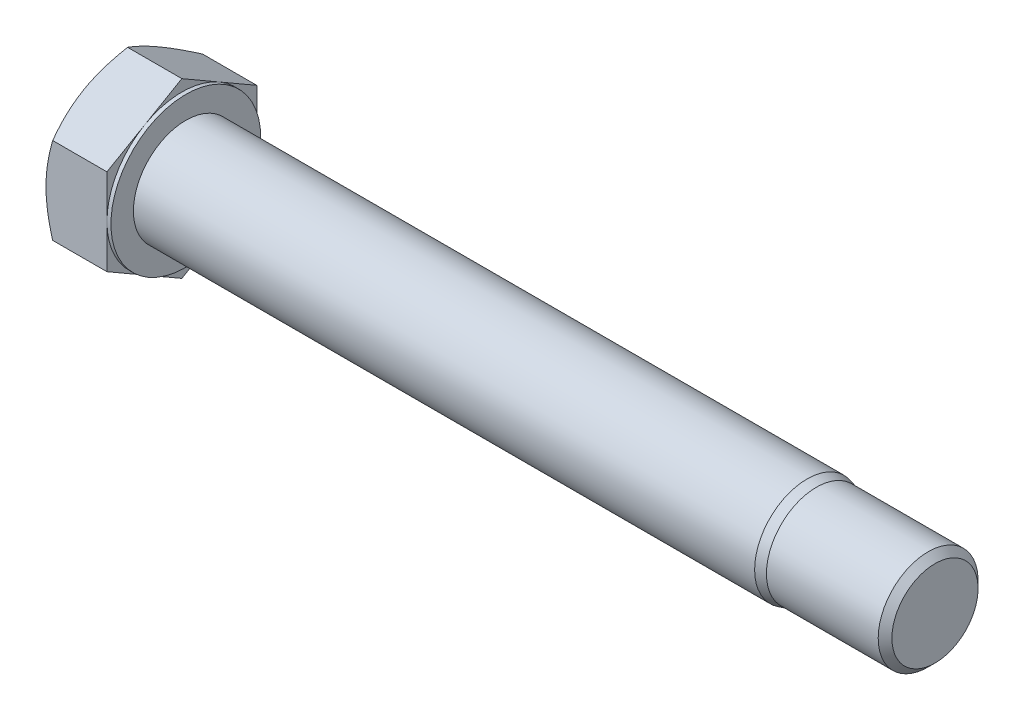
SolidWorks part; units mm, degrees
extrude "BaseHead" add sketch "HeadSke" along normal blind 13
sketch "HeadSke" plane through (0, 0, 0) normal (1, 0, 0) x (0, 0, -1)
  line L0 (15, 8.6603) -> (15, -8.6603)
  line L1 (-15, 8.6603) -> (-15, -8.6603)
  line L2 (15, -8.6603) -> (0, -17.3205)
  line L3 (0, -17.3205) -> (-15, -8.6603)
  line L4 (15, 8.6603) -> (0, 17.3205)
  line L5 (0, 17.3205) -> (-15, 8.6603)
  line L6 (0, 17.3205) -> (0, -17.3205) construction
  dimension "Width_flats" = 30
  dimension "D2" = 120
ref_plane "Plane1" through (0, 0, 0) normal (0, 0, 1) x (1, 0, 0)
ref_plane "Plane2" through (0, 0, 0) normal (0, 1, 0) x (1, 0, 0)
ref_plane "Plane3" through (0, 0, 0) normal (1, 0, 0) x (0, 0, -1)
sketch "BodySke" plane through (0, 0, 0) normal (0, 0, 1) x (1, 0, 0)
  line L0 (0, 10.5) -> (0, 0)
  line L2 (0, 0) -> (163, 0)
  line L4 (163, 0) -> (163, 8.626)
  line L5 (13, 17.3205) -> (13, 8.6603) construction
  line L6 (163, 8.626) -> (161.626, 10)
  line L7 (0, 0) -> (194.2747, 0) construction
  line L8 (163, -8.626) -> (161.626, -10) construction
  line L9 (0, -10) -> (161.626, -10) construction
  line L10 (15.5, 15.24) -> (15.5, -1.27) construction
  line L11 (139.25, 10) -> (137.384, 10.5)
  line L12 (13, 8.6603) -> (13, -8.6603) construction
  line L13 (137.384, 10.5) -> (0, 10.5)
  line L15 (139.25, 10) -> (161.626, 10)
  dimension "D1" = 75
  dimension "Diameter" = 20
  dimension "Thread_nom" = 23.75
revolve "BaseBody" add sketch "BodySke" angle 360 about L7
cosmetic thread "ThreadCosmetic" [suppressed] parameters "Thread_length"=21.25, "Thread_minor"=17.252
sketch "Sketch3" plane through (0, 0, 0) normal (0, 1, 0) x (1, 0, 0)
  line L0 (3.75, 21.4952) -> (-3.75, 8.5048)
  line L1 (3.75, 21.4952) -> (-6.1958, 27.2374)
  line L2 (-3.75, 8.5048) -> (-13.6958, 14.247)
  line L3 (-6.1958, 27.2374) -> (-13.6958, 14.247)
  line L4 (0, 15) -> (0, 0) construction
  line L6 (0, 0) -> (99.06, 0) construction
  dimension "Head_ch_ang" = 30
revolve "HeadChamfer" cut sketch "Sketch3" angle 360 about L6
sketch "BearingSke" plane through (0, 0, 0) normal (0, 0, 1) x (1, 0, 0)
  line L0 (13, 17.3205) -> (1.3397, 17.3205) construction
  line L1 (13, 17.3205) -> (13, 8.6603) construction
  line L2 (13, 15) -> (12.2, 15)
  line L3 (13, 15) -> (13, 17.3205)
  line L4 (13, 17.3205) -> (12.2, 17.3205)
  line L5 (0, 0) -> (95.25, 0) construction
  line L6 (0, 0) -> (194.2747, 0) construction
  line L7 (12.2, 15) -> (12.2, 17.3205)
  dimension "Bearing_ht" = 0.8
  dimension "Bearing_dia" = 30
revolve "BearingFace" cut sketch "BearingSke" angle 360 about L5
fillet "HeadFillet" [suppressed] radius 0.8
sketch "ThdSchSke" plane through (0, 0, 0) normal (0, 0, 1) x (1, 0, 0)
  line L0 (141.75, -8.626) -> (140.7879, -10)
  line L1 (141.75, -8.626) -> (142.7121, -10)
  line L2 (142.7121, -10) -> (142.7121, -12.5)
  line L3 (-3.175, 0) -> (5.1513, 0) construction
  line L5 (142.7121, -12.5) -> (140.7879, -12.5)
  line L6 (140.7879, -12.5) -> (140.7879, -10)
  dimension "Thread_minor" = 17.252
  dimension "Diameter" = 20
  dimension "Start" = 141.75
revolve "ThreadSchematic" [suppressed] cut sketch "ThdSchSke" angle 360 about L3
pattern_linear "ThdSchPat" [suppressed]
equation "\"Thread_minor@ThreadCosmetic\" = \"Minor_dia@BodySke\""
equation "\"Thread_length@ThreadCosmetic\" = \"Thread_nom@BodySke\" - \"Advance@BodySke\""
equation "\"Thread_minor@ThdSchSke\" = \"Minor_dia@BodySke\""
equation "\"Diameter@ThdSchSke\" = \"Diameter@BodySke\""
equation "\"Overcut@ThdSchSke\" = \"Diameter@BodySke\" * 1.25"
equation "\"Start@ThdSchSke\" = \"Head_ht@BaseHead\" + \"Length@BodySke\" - \"Thread_length@ThreadCosmetic\"  '---Non-countersunk---"
equation "\"Num_threads@ThdSchPat\" = int( \"Thread_length@ThreadCosmetic\" / \"Advance@BodySke\" + 0.999 )  + 1"
equation "\"Advance@ThdSchPat\" = \"Thread_length@ThreadCosmetic\" /  (\"Num_threads@ThdSchPat\" - 1) 'relax it"
equation "\"Num_threads@ThdSchPat\" = \"Num_threads@ThdSchPat\" - sgn( \"Num_threads@ThdSchPat\" - 1) '---chamfered tips only---"
